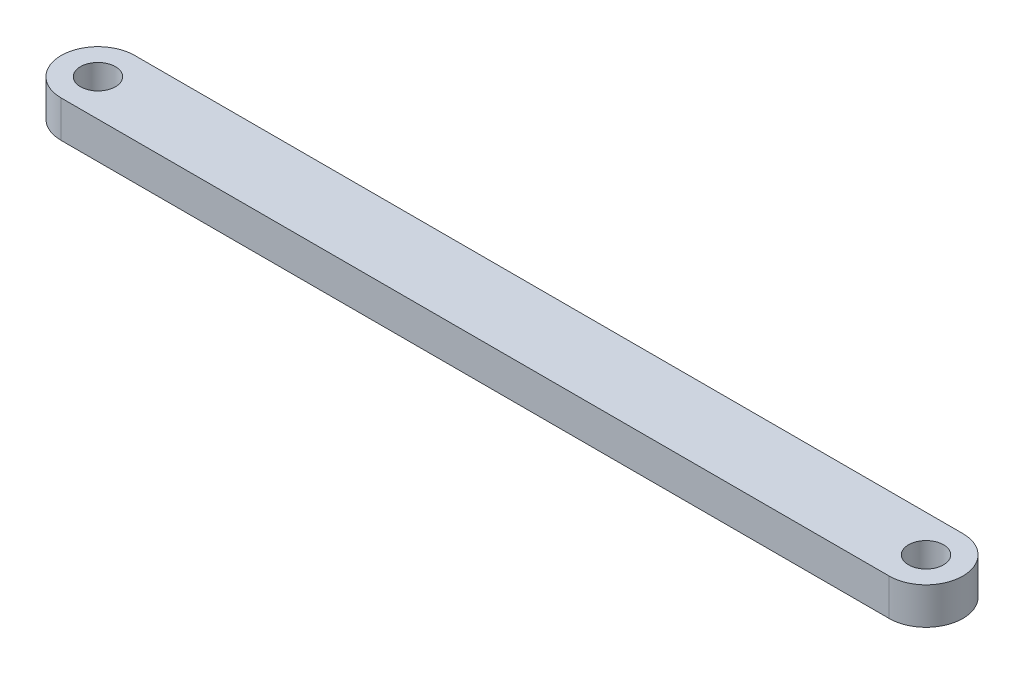
SolidWorks part; units mm, degrees
ref_plane "Front Plane" through (0, 0, 0) normal (0, 0, 1) x (1, 0, 0)
ref_plane "Top Plane" through (0, 0, 0) normal (0, 1, 0) x (1, 0, 0)
ref_plane "Right Plane" through (0, 0, 0) normal (1, 0, 0) x (0, 0, -1)
sketch "Sketch1" plane through (0, 0, 0) normal (0, 1, 0) x (1, 0, 0)
  line L0 (22.5, 0) -> (-22.5, 0) construction
  line L1 (22.5, -2) -> (-22.5, -2)
  line L2 (22.5, 2) -> (-22.5, 2)
  arc A0 (22.5, -2) -> (22.5, 2) centre (22.5, 0) ccw
  arc A1 (-22.5, 2) -> (-22.5, -2) centre (-22.5, 0) ccw
  circle A2 centre (-22.5, 0) radius 0.95
  circle A3 centre (22.5, 0) radius 0.95
  point P2 (0, 0)
  dimension "D2" = 2
  dimension "D3" = 1.9
  dimension "D1" = 45
extrude "Boss-Extrude1" add sketch "Sketch1" along normal mid plane 2
